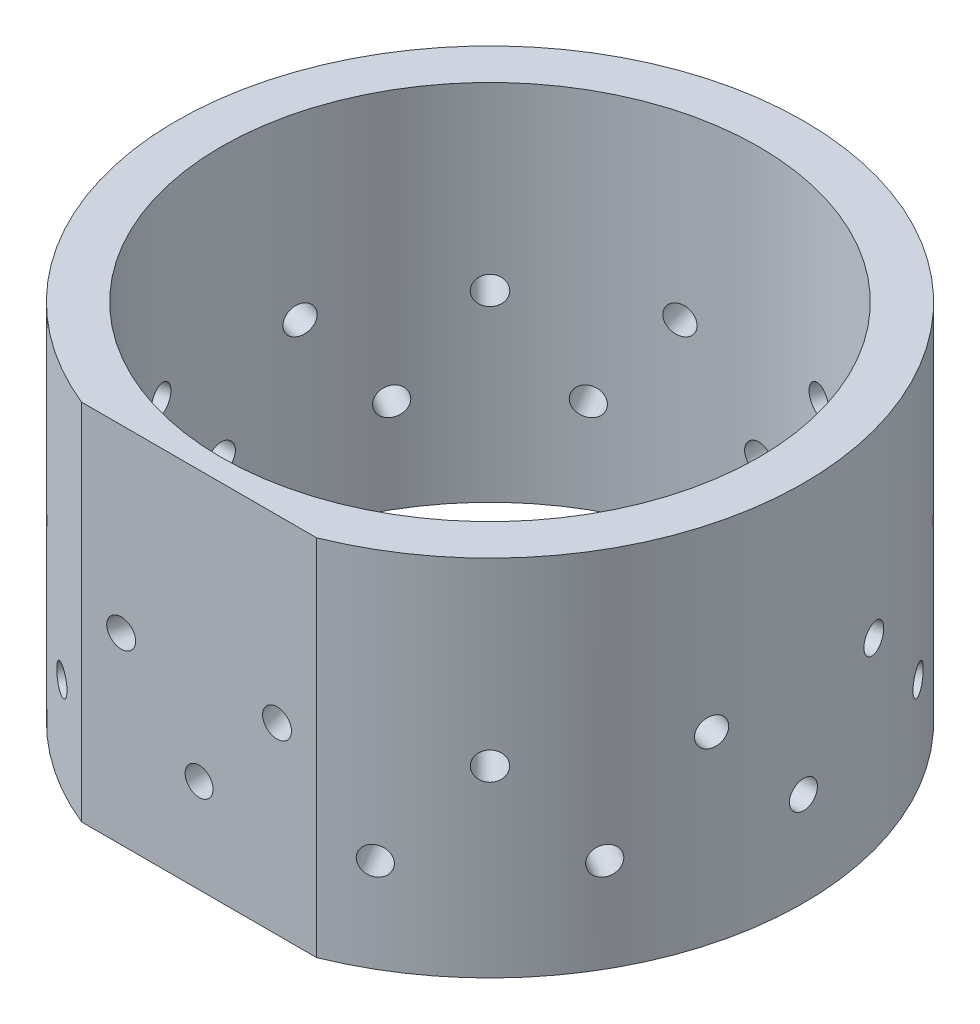
SolidWorks part; units mm, degrees
ref_plane "Front Plane" through (0, 0, 0) normal (0, 0, 1) x (1, 0, 0)
ref_plane "Top Plane" through (0, 0, 0) normal (0, 1, 0) x (1, 0, 0)
ref_plane "Right Plane" through (0, 0, 0) normal (1, 0, 0) x (0, 0, -1)
sketch "Sketch1" plane through (0, 0, 0) normal (0, 1, 0) x (1, 0, 0)
  circle A0 centre (0, 0) radius 76.327
  circle A1 centre (0, 0) radius 89.027
  dimension "D1" = 152.654
  dimension "D2" = 178.054
extrude "Boss-Extrude1" add sketch "Sketch1" along normal blind 103.1875
sketch "Sketch2" plane through (0, 0, 0) normal (0, -1, 0) x (1, 0, 0)
  line L0 (0, 0) -> (0, -89.027)
  circle A0 centre (0, 0) radius 89.027 construction
ref_plane "Plane1" through (0, 0, -89.027) normal (0, 0, -1) x (-1, 0, 0)
sketch "Sketch3" plane through (0, 0, -89.027) normal (0, 0, -1) x (-1, 0, 0)
  line L0 (0, 0) -> (0, 26.67) construction
  circle A0 centre (0, 26.67) radius 3.9688
  dimension "D1" = 7.9375
extrude "Cut-Extrude1" cut sketch "Sketch3" against normal blind 15.24
pattern_circular "CirPattern1" count 12 over 360 about axis through (0, 103.1875, 0) along (0, -1, 0) of "Cut-Extrude1"
ref_plane "Plane2" through (-23.0419, 0, 85.9935) normal (-0.2588, 0, 0.9659) x (0, -1, 0)
sketch "Sketch4" plane through (-23.0419, 0, 85.9935) normal (-0.2588, 0, 0.9659) x (0, -1, 0)
  line L0 (0, 0) -> (-52.07, 0) construction
  circle A0 centre (-52.07, 0) radius 3.9687
  dimension "D2" = 7.9375
  dimension "D1" = 52.07
extrude "Cut-Extrude2" cut sketch "Sketch4" against normal blind 15.24 contours A0
pattern_circular "CirPattern2" count 12 over 360 about axis through (0, 103.1875, 0) along (0, -1, 0) of "Cut-Extrude2"
ref_plane "Plane3" through (0, 0, 82.55) normal (0, 0, 1) x (1, 0, 0)
split "Split1" trim tools "Plane3" bodies to split 108 resulting bodies 110
